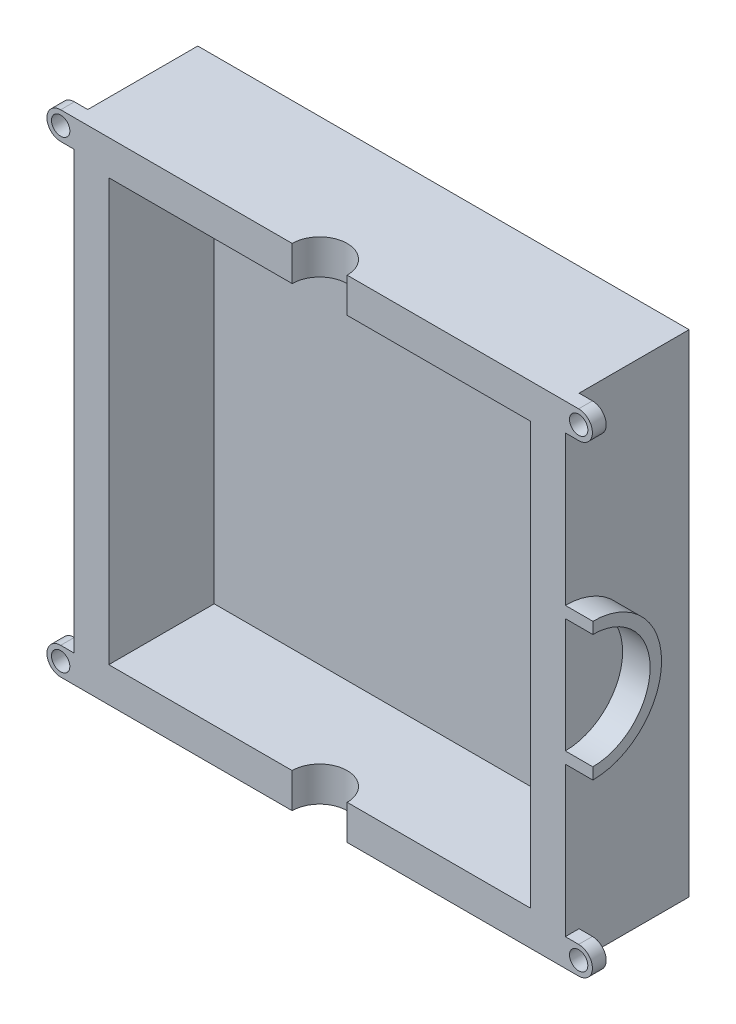
SolidWorks part; units mm, degrees
ref_plane "前视基准面" through (0, 0, 0) normal (0, 0, 1) x (1, 0, 0)
ref_plane "上视基准面" through (0, 0, 0) normal (0, 1, 0) x (1, 0, 0)
ref_plane "右视基准面" through (0, 0, 0) normal (1, 0, 0) x (0, 0, -1)
sketch "草图1" plane through (0, 0, 0) normal (0, 0, 1) x (1, 0, 0)
  line L1 (-53.59, -53.59) -> (53.59, -53.59)
  line L2 (-53.59, -53.59) -> (-53.59, 53.59)
  line L3 (-53.59, 53.59) -> (53.59, 53.59)
  line L4 (53.59, -53.59) -> (53.59, 53.59)
  line L5 (-53.59, -53.59) -> (53.59, 53.59) construction
  line L6 (-53.59, 53.59) -> (53.59, -53.59) construction
  point P0 (0, 0)
  dimension "D1" = 107.18
extrude "凸台-拉伸1" add sketch "草图1" along normal blind 27
sketch "草图2" plane through (0, 0, 27) normal (0, 0, 1) x (1, 0, 0)
  line L1 (-46, 46) -> (46, 46)
  line L2 (-46, 46) -> (-46, -46)
  line L3 (-46, -46) -> (46, -46)
  line L4 (46, 46) -> (46, -46)
  line L5 (-46, 46) -> (46, -46) construction
  line L6 (-46, -46) -> (46, 46) construction
  point P0 (0, 0)
  dimension "D1" = 92
extrude "切除-拉伸1" cut sketch "草图2" against normal blind 23
sketch "草图3" plane through (0, 53.59, 0) normal (0, 1, 0) x (1, 0, 0)
  line L0 (53.59, -27) -> (-53.59, -27) construction
  circle A0 centre (0, -27) radius 6
extrude "切除-拉伸2" cut sketch "草图3" against normal through all
sketch "草图5" plane through (53.59, 0, 0) normal (1, 0, 0) x (0, 0, -1)
  line L0 (-27, 46) -> (-27, -46) construction
  line L1 (-27, 15) -> (-27, -15)
  arc A0 (-27, -15) -> (-27, 15) centre (-27, 0) ccw
  arc A2 (-27, -12.5) -> (-27, 12.5) centre (-27, 0) ccw
  line M6 (-27, 53.59) -> (-27, -53.59)
  dimension "D1" = 15
  dimension "D2" = 25
extrude "凸台-拉伸3" add sketch "草图5" along normal blind 6 contours A2 L1 A0 M6
sketch "草图7" plane through (0, 0, 27) normal (0, 0, 1) x (1, 0, 0)
  line L0 (0, 58.4894) -> (0, -27.448) construction
  line L1 (-56.5, 50.59) -> (-49.4735, 50.59) construction
  line L2 (-56.5, 53.59) -> (-49.4735, 53.59)
  line L3 (-56.5, 47.59) -> (-49.4735, 47.59)
  line L4 (53.59, 53.59) -> (6, 53.59) construction
  line L5 (-73.14, 0) -> (28.0534, 0) construction
  line L6 (51.1723, 53.59) -> (56.5, 53.59)
  line L9 (-49.4735, 53.59) -> (-49.4735, 47.59)
  line L10 (51.1723, 53.59) -> (51.1723, 47.59)
  line L11 (51.1723, 50.59) -> (56.5, 50.59) construction
  line L12 (51.1723, 47.59) -> (56.5, 47.59)
  line L13 (51.1723, -50.59) -> (56.5, -50.59) construction
  line L14 (-56.5, -50.59) -> (-49.4735, -50.59) construction
  line L15 (51.1723, -47.59) -> (56.5, -47.59)
  line L16 (51.1723, -53.59) -> (51.1723, -47.59)
  line L17 (-49.4735, -53.59) -> (-49.4735, -47.59)
  line L18 (51.1723, -53.59) -> (56.5, -53.59)
  line L19 (-56.5, -47.59) -> (-49.4735, -47.59)
  line L20 (-56.5, -53.59) -> (-49.4735, -53.59)
  arc A0 (-56.5, 53.59) -> (-56.5, 47.59) centre (-56.5, 50.59) ccw
  arc A1 (56.5, 47.59) -> (56.5, 53.59) centre (56.5, 50.59) ccw
  circle A5 centre (-56.5, 50.59) radius 2
  circle A6 centre (56.5, 50.59) radius 2
  circle A7 centre (-56.5, -50.59) radius 2
  arc A8 (56.5, -47.59) -> (56.5, -53.59) centre (56.5, -50.59) cw
  arc A9 (-56.5, -53.59) -> (-56.5, -47.59) centre (-56.5, -50.59) cw
  circle A10 centre (56.5, -50.59) radius 2
  point P5 (0, 50.59)
  point P16 (0, -50.59)
  dimension "D1" = 3
  dimension "D2" = 113
extrude "凸台-拉伸4" add sketch "草图7" against normal blind 3
